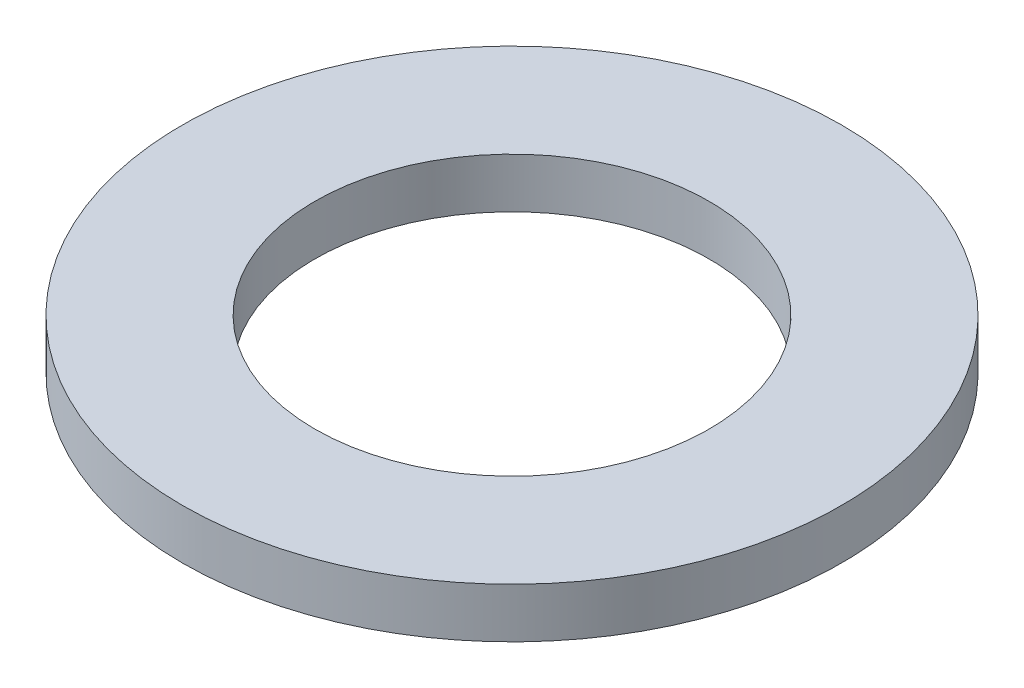
SolidWorks part; units mm, degrees
material "Nylon 6/10 Red"
ref_plane "Front Plane" through (0, 0, 0) normal (0, 0, 1) x (1, 0, 0)
ref_plane "Top Plane" through (0, 0, 0) normal (0, 1, 0) x (1, 0, 0)
ref_plane "Right Plane" through (0, 0, 0) normal (1, 0, 0) x (0, 0, -1)
sketch "Sketch1" plane through (0, 0, 0) normal (0, 1, 0) x (1, 0, 0)
  circle A0 centre (0, 0) radius 1.6764
  circle A1 centre (0, 0) radius 1.0033
  dimension "D1" = 3.3528
  dimension "D2" = 2.0066
extrude "Boss-Extrude1" add sketch "Sketch1" along normal blind 0.254
